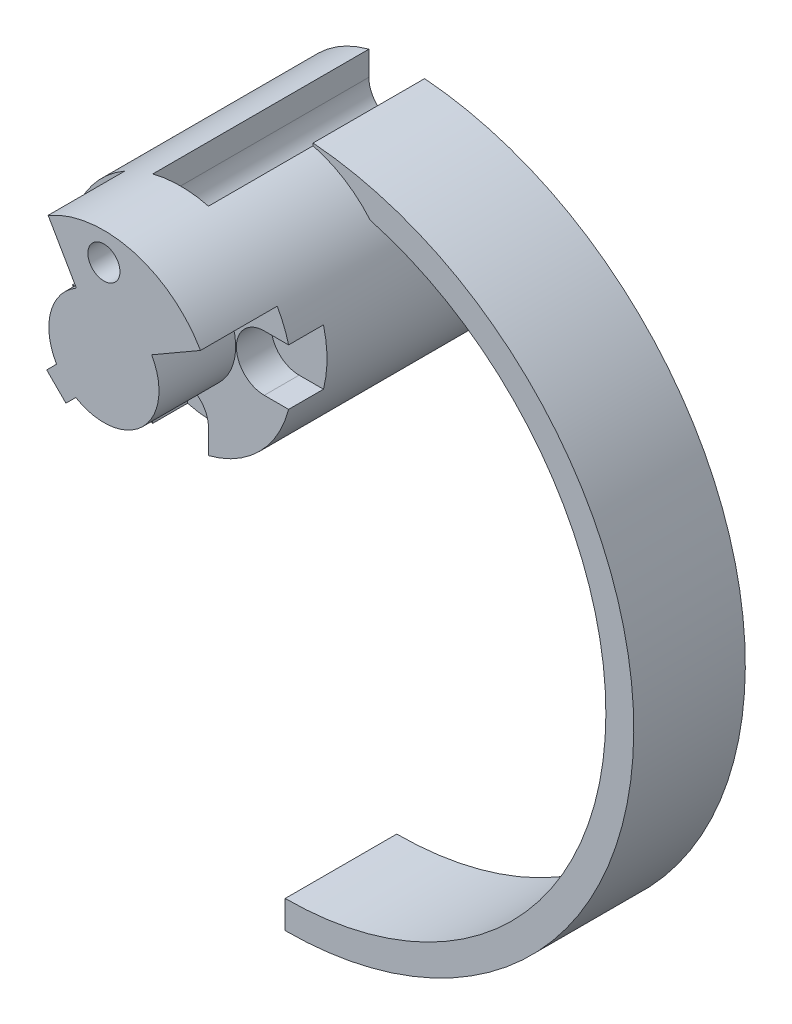
SolidWorks part; units mm, degrees
ref_plane "Front Plane" through (0, 0, 0) normal (0, 0, 1) x (1, 0, 0)
ref_plane "Top Plane" through (0, 0, 0) normal (0, 1, 0) x (1, 0, 0)
ref_plane "Right Plane" through (0, 0, 0) normal (1, 0, 0) x (0, 0, -1)
sketch "Sketch1" plane through (0, 0, 0) normal (0, 0, 1) x (1, 0, 0)
  line L0 (0, 0) -> (0, -42) construction
  line L1 (0, -42) -> (0, -40)
  circle A0 centre (0, 0) radius 8 construction
  circle A1 centre (0, 0) radius 6 construction
  circle A2 centre (0, 6) radius 1.15
  circle A3 centre (-6, 0) radius 1.15
  circle A4 centre (0, -6) radius 1.15
  circle A5 centre (6, 0) radius 1.15
  arc A6 (0, 8) -> (0, -8) centre (0, 0) ccw
  arc A7 (0, 8) -> (0, -42) centre (0, -17) cw
  arc A8 (6.0995, 5.1765) -> (0, -40) centre (0, -17) cw
  arc A9 (0, -8) -> (6.0995, 5.1765) centre (0, 0) ccw
  point P12 (0, 8)
  dimension "D1" = 16
  dimension "D2" = 12
  dimension "D3" = 2.3
  dimension "D4" = 2
  dimension "D5" = 50
extrude "Boss-Extrude1" add sketch "Sketch1" along normal blind 8
sketch "Sketch4" plane through (0, 0, 0) normal (0, 0, -1) x (-1, 0, 0)
  circle A0 centre (0, 0) radius 8
  circle A1 centre (0, 6) radius 1.15 construction
  circle A2 centre (-6, 0) radius 1.15 construction
  circle A3 centre (0, -6) radius 1.15 construction
  circle A4 centre (6, 0) radius 1.15 construction
  circle A5 centre (0, 6) radius 1.15
  circle A6 centre (-6, 0) radius 1.15
  circle A7 centre (0, -6) radius 1.15
  circle A8 centre (6, 0) radius 1.15
extrude "Boss-Extrude2" add sketch "Sketch4" along normal blind 13
sketch "Sketch3" plane through (0, 0, 8) normal (0, 0, 1) x (1, 0, 0)
  line L0 (6, 2) -> (10, 2)
  line L1 (10, 2) -> (10, -2)
  line L2 (10, -2) -> (6, -2)
  line L3 (2, -6) -> (2, -10)
  line L4 (2, -10) -> (-2, -10)
  line L5 (-2, -10) -> (-2, -6)
  line L6 (-6, -2) -> (-10, -2)
  line L7 (-10, -2) -> (-10, 2)
  line L8 (-10, 2) -> (-6, 2)
  line L9 (-2, 6) -> (-2, 10)
  line L10 (-2, 10) -> (2, 10)
  line L11 (2, 10) -> (2, 6)
  circle A0 centre (6, 0) radius 2 construction
  circle A1 centre (0, 6) radius 2 construction
  circle A2 centre (-6, 0) radius 2 construction
  circle A3 centre (0, -6) radius 2 construction
  arc A4 (2, 6) -> (-2, 6) centre (0, 6) cw
  arc A5 (-6, 2) -> (-6, -2) centre (-6, 0) cw
  arc A6 (-2, -6) -> (2, -6) centre (0, -6) cw
  arc A7 (6, -2) -> (6, 2) centre (6, 0) cw
  dimension "D1" = 4
  dimension "D2" = 4
extrude "Cut-Extrude3" cut sketch "Sketch3" against normal offset from surface (15.5 mm away) 5.5 up to face at (-1.15, -6, -13)
sketch "Sketch5" plane through (0, 0, -13) normal (0, 0, -1) x (-1, 0, 0)
  line L0 (-3.4208, 1.975) -> (-6.9282, 4)
  line L1 (4, 6.9282) -> (1.975, 3.4208)
  line L7 (2.0172, -3.3961) -> (2.7243, -4.1032)
  line L8 (2.7243, -4.1032) -> (4.1032, -2.7243)
  line L9 (4.1032, -2.7243) -> (3.3961, -2.0172)
  line L10 (0, 0) -> (2.3478, 0) construction
  circle A1 centre (0, 0) radius 8 construction
  arc A2 (-6.9282, 4) -> (4, 6.9282) centre (0, 0) ccw
  arc A3 (-3.4208, 1.975) -> (2.0172, -3.3961) centre (0, 0) ccw
  arc A4 (3.3961, -2.0172) -> (1.975, 3.4208) centre (0, 0) ccw
  dimension "D2" = 3.95
  dimension "D1" = 90
  dimension "D3" = 45
  dimension "D4" = 1
  dimension "D5" = 1.95
  dimension "D6" = 30
extrude "Cut-Extrude4" cut sketch "Sketch5" against normal up to surface (5.5 mm away) up to face at (4.85, 0, -7.5)
sketch "Sketch6" plane through (0, 0, 8) normal (0, 0, 1) x (1, 0, 0)
  line L0 (5.6569, 5.6569) -> (0, 0)
  line L1 (0, 0) -> (-5.6569, 5.6569)
  arc A0 (-5.6569, 5.6569) -> (5.6569, 5.6569) centre (0, 0) ccw
  arc A1 (-2, 7.746) -> (-7.746, 2) centre (0, 0) ccw construction
extrude "Boss-Extrude3" add sketch "Sketch6" against normal offset from surface (13 mm away) 2.5 up to face at (-0.3679, -1.2187, -7.5)
sketch "Sketch7" plane through (0, 0, 8) normal (0, 0, 1) x (1, 0, 0)
  line L0 (3.3019, 3.7547) -> (2.0213, -0.0348)
  line L3 (5.9434, 0.7509) -> (3.3019, 3.7547)
  line L4 (-1.9811, 2.2528) -> (-3.3019, 3.7547)
  line L5 (2.0213, -0.0348) -> (2.9957, 0.1604)
  line L6 (4.969, 0.5557) -> (5.9434, 0.7509)
  arc A0 (4.969, 0.5557) -> (-3.3019, 3.7547) centre (0, 0) cw
  arc A1 (-1.9811, 2.2528) -> (2.9957, 0.1604) centre (0, 0) ccw
  dimension "D1" = 5
  dimension "D2" = 2
  dimension "D3" = 60
  dimension "D4" = 4
  dimension "D5" = 60
extrude "Cut-Extrude5" [suppressed] cut sketch "Sketch7" against normal blind 0.5
mirror "Mirror2" about plane through (0, 0, 0) normal (0, 0, 1) of bodies 106
delete or keep bodies "Body-Delete/Keep 1" type keep bodies bodies 108
equation "\"LENGTH\"= 3 + 10"
equation "\"D1@Boss-Extrude2\"=\"LENGTH\""
